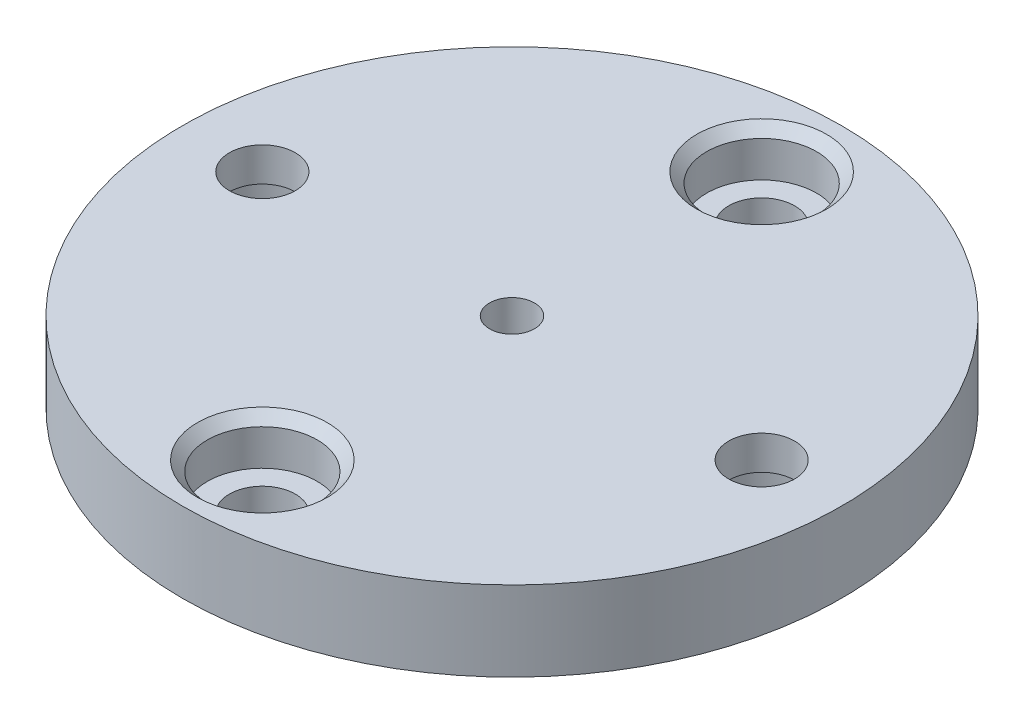
SolidWorks part; units mm, degrees
ref_plane "Front Plane" through (0, 0, 0) normal (0, 0, 1) x (1, 0, 0)
ref_plane "Top Plane" through (0, 0, 0) normal (0, 1, 0) x (1, 0, 0)
ref_plane "Right Plane" through (0, 0, 0) normal (1, 0, 0) x (0, 0, -1)
sketch "Sketch1" plane through (0, 0, 0) normal (0, 1, 0) x (1, 0, 0)
  circle A5 centre (0, 0) radius 33
  dimension "D1" = 66
extrude "Boss-Extrude1" add sketch "Sketch1" along normal blind 8
sketch "Sketch2" plane through (0, 0, 0) normal (0, -1, 0) x (-1, 0, 0)
  circle A0 centre (0, 0) radius 15.5
  dimension "D1" = 31
extrude "Boss-Extrude2" add sketch "Sketch2" along normal blind 3
sketch "Sketch4" plane through (0, 0, 0) normal (0, -1, 0) x (1, 0, 0)
  circle A0 centre (-17.6777, -17.6777) radius 3.05
  dimension "D2" = 6.1
extrude "Cut-Extrude2" cut sketch "Sketch4" against normal blind 5
chamfer "Chamfer1" distance 0.5 angle 45 1 edges at (0, -3, -15.5)
sketch "Sketch5" plane through (0, 0, 0) normal (0, -1, 0) x (1, 0, 0)
  line L0 (0, 33) -> (0, -33) construction
  line L1 (-33, 0) -> (33, 0) construction
  circle A0 centre (0, 0) radius 33 construction
hole_wizard "CBORE for M6 Hex Socket Thin Head Cap Screw2" positions "Sketch7" profile "Sketch8" counterbore size "M6" standard "DIN" end condition through all
sketch "Sketch7" plane through (0, 0, 0) normal (0, -1, 0) x (-1, 0, 0)
  line L0 (33, 0) -> (-33, 0) construction
  point P0 (25, 0)
  point P4 (-25, 0)
  dimension "D1" = 25
  dimension "D2" = 25
sketch "Sketch8" plane through (-25, 0, 0) normal (1, 0, 0) x (0, 0, -1)
  line L0 (0, 0) -> (0, 8)
  line L1 (0, 8) -> (3.3, 8)
  line L3 (3.3, 8) -> (3.3, 4.6)
  line L4 (5.5, 4.6) -> (3.3, 4.6)
  line L5 (5.5, 4.6) -> (5.5, 1)
  line L6 (5.5, 1) -> (6.5, 0)
  line L7 (6.5, 0) -> (0, 0)
  line L8 (-5.5, 1) -> (-6.5, 0) construction
  line L11 (0, -6.35) -> (0, 107.95) construction
  dimension "Thru Hole Dia." = 6.6
  dimension "Thru Hole Depth" = 8
  dimension "C'Bore Dia." = 11
  dimension "C'Bore Depth" = 4.6
  dimension "Near C'Sink Dia." = 13
  dimension "Near C'Sink Angle" = 90
hole_wizard "CBORE for M6 Hex Socket Thin Head Cap Screw3" positions "Sketch9" profile "Sketch10" counterbore size "M6" standard "DIN" end condition through all
sketch "Sketch9" plane through (0, 8, 0) normal (0, 1, 0) x (1, 0, 0)
  line L0 (0, -33) -> (0, 33) construction
  point P0 (0, 25)
  point P4 (0, -25)
  dimension "D1" = 25
  dimension "D2" = 25
sketch "Sketch10" plane through (0, 8, -25) normal (1, 0, 0) x (0, 0, 1)
  line L0 (0, 0) -> (0, 11)
  line L1 (0, 11) -> (3.3, 11)
  line L3 (3.3, 11) -> (3.3, 4.6)
  line L4 (5.5, 4.6) -> (3.3, 4.6)
  line L5 (5.5, 4.6) -> (5.5, 1)
  line L6 (5.5, 1) -> (6.5, 0)
  line L7 (6.5, 0) -> (0, 0)
  line L8 (-5.5, 1) -> (-6.5, 0) construction
  line L11 (0, -6.35) -> (0, 107.95) construction
  dimension "Thru Hole Dia." = 6.6
  dimension "Thru Hole Depth" = 11
  dimension "C'Bore Dia." = 11
  dimension "C'Bore Depth" = 4.6
  dimension "Near C'Sink Dia." = 13
  dimension "Near C'Sink Angle" = 90
hole_wizard "CSK for M4 Countersunk Flat Head Screw1" positions "Sketch11" profile "Sketch12" countersink size "M4" standard "DIN" end condition through all
sketch "Sketch11" plane through (0, -3, 0) normal (0, -1, 0) x (-1, 0, 0)
  point P0 (0, 0)
sketch "Sketch12" plane through (0, -3, 0) normal (1, 0, 0) x (0, 0, -1)
  line L0 (0, 0) -> (0, 11)
  line L1 (0, 11) -> (2.25, 11)
  line L2 (2.25, 11) -> (2.25, 2.45)
  line L3 (2.25, 2.45) -> (4.7, 0)
  line L5 (4.7, 0) -> (0, 0)
  line L6 (-2.25, 2.45) -> (-4.7, 0) construction
  line L11 (0, -6.35) -> (0, 107.95) construction
  dimension "Thru Hole Dia." = 4.5
  dimension "Thru Hole Depth" = 11
  dimension "Near C'Sink Dia." = 9.4
  dimension "Near C'Sink Angle" = 90
